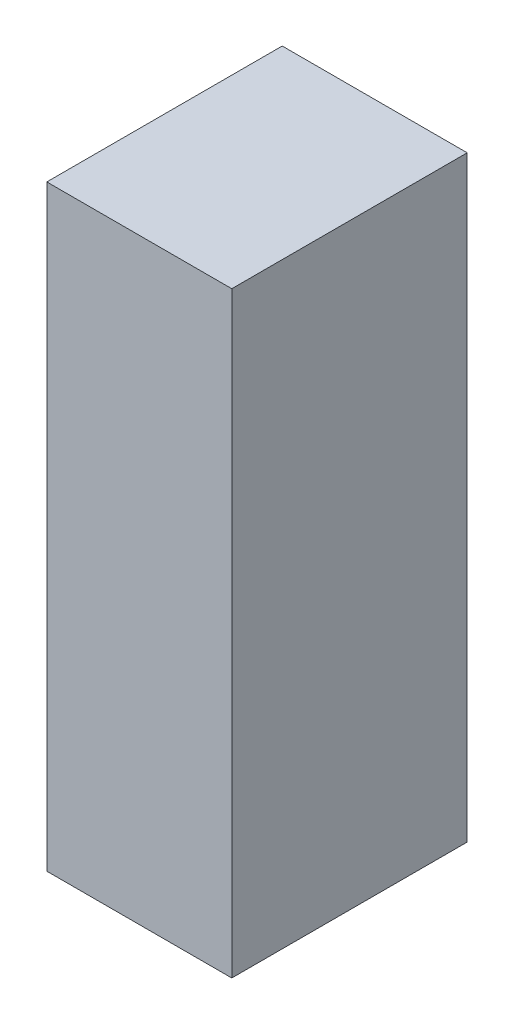
SolidWorks part; units mm, degrees
ref_plane "前视基准面" through (0, 0, 0) normal (0, 0, 1) x (1, 0, 0)
ref_plane "上视基准面" through (0, 0, 0) normal (0, 1, 0) x (1, 0, 0)
ref_plane "右视基准面" through (0, 0, 0) normal (1, 0, 0) x (0, 0, -1)
other "Configuration Table"
sketch "草图1" plane through (0, 0, 0) normal (0, 0, 1) x (1, 0, 0)
  line L8 (-22, -71) -> (22, -71)
  line L9 (22, -71) -> (22, 71)
  line L10 (22, 71) -> (-22, 71)
  line L11 (-22, 71) -> (-22, -71)
extrude "设备占位" add sketch "草图1" along normal blind 56
